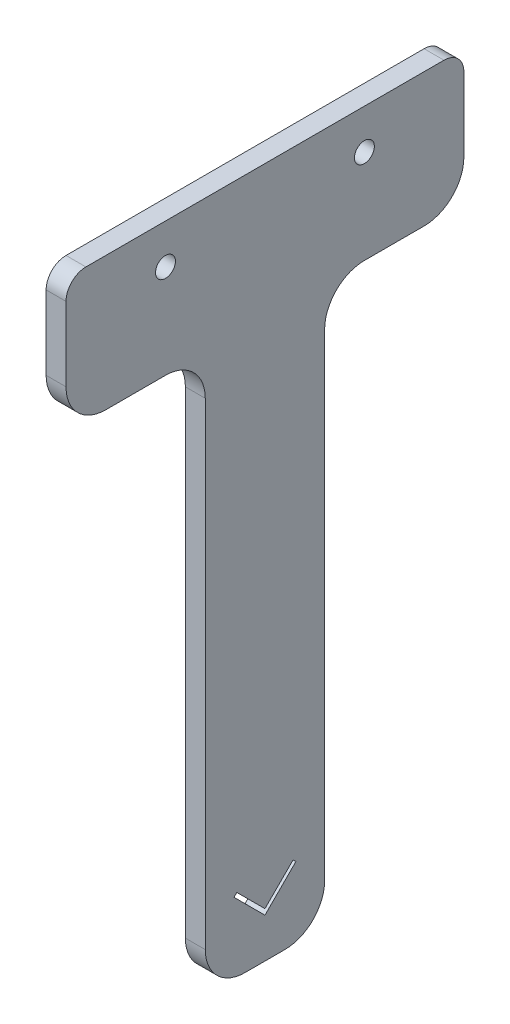
SolidWorks part; units mm, degrees
material "Balsa"
ref_plane "Front Plane" through (0, 0, 0) normal (0, 0, 1) x (1, 0, 0)
ref_plane "Top Plane" through (0, 0, 0) normal (0, 1, 0) x (1, 0, 0)
ref_plane "Right Plane" through (0, 0, 0) normal (1, 0, 0) x (0, 0, -1)
sketch "Sketch3" plane through (0, 0, 0) normal (1, 0, 0) x (0, 0, -1)
  line L1 (-57.15, -110.236) -> (57.15, -110.236)
  line L2 (-63.5, -103.886) -> (-63.5, 103.886)
  line L3 (-57.15, 110.236) -> (57.15, 110.236)
  line L4 (63.5, -103.886) -> (63.5, 103.886)
  line L5 (-63.5, -110.236) -> (63.5, 110.236) construction
  line L6 (-63.5, 110.236) -> (63.5, -110.236) construction
  line L11 (0, 0) -> (38.1, 84.836) construction
  line L12 (-38.1, 84.836) -> (0, 0) construction
  arc A0 (-57.15, -110.236) -> (-63.5, -103.886) centre (-57.15, -103.886) cw
  arc A1 (63.5, -103.886) -> (57.15, -110.236) centre (57.15, -103.886) cw
  arc A2 (63.5, 103.886) -> (57.15, 110.236) centre (57.15, 103.886) ccw
  arc A3 (-63.5, 103.886) -> (-57.15, 110.236) centre (-57.15, 103.886) cw
  point P0 (0, 0)
  point P6 (0, 0)
  point P26 (38.1, -67.564)
  dimension "D7" = 6.35
  dimension "D1" = 220.472
  dimension "D2" = 127
  dimension "D3" = 76.2
  dimension "D4" = 152.4
extrude "Boss-Extrude2" add sketch "Sketch3" along normal blind 6.35
sketch "Sketch4" plane through (6.35, 0, 0) normal (1, 0, 0) x (0, 0, -1)
  line L0 (-57.15, -110.236) -> (57.15, -110.236) construction
  line L5 (0, -95.7399) -> (-8.9803, -86.7597)
  line L6 (-8.9803, -86.7597) -> (-9.8783, -87.6577)
  line L8 (-9.8783, -87.6577) -> (0, -97.536)
  line L9 (0, -97.536) -> (9.8783, -87.6577)
  line L10 (9.8783, -87.6577) -> (8.9803, -86.7597)
  line L11 (8.9803, -86.7597) -> (0, -95.7399)
  line L12 (0, 55) -> (0, -55) construction
  dimension "D1" = 12.7
  dimension "D2" = 12.7
  dimension "D3" = 1.27
extrude "Cut-Extrude1" cut sketch "Sketch4" against normal up to next
sketch "Sketch5" plane through (6.35, 0, 0) normal (1, 0, 0) x (0, 0, -1)
  line L0 (-31.75, 97.536) -> (31.75, 97.536) construction
  line L1 (31.75, 97.536) -> (63.5, 97.536) construction
  line L2 (63.5, -103.886) -> (63.5, 103.886) construction
  line L3 (-31.75, 97.536) -> (-63.5, 97.536) construction
  line L4 (-63.5, 103.886) -> (-63.5, -103.886) construction
  line L5 (57.15, 110.236) -> (-57.15, 110.236) construction
  circle A0 centre (-31.75, 97.536) radius 3.175
  circle A1 centre (31.75, 97.536) radius 3.175
  dimension "D1" = 6.35
  dimension "D2" = 63.5
  dimension "D3" = 12.7
extrude "Cut-Extrude2" cut sketch "Sketch5" against normal through all both and the other way through all
sketch "Sketch6" plane through (6.35, 0, 0) normal (1, 0, 0) x (0, 0, -1)
  line L0 (-19.05, -97.536) -> (-19.05, 54.864)
  line L1 (19.05, -97.536) -> (19.05, 54.864)
  line L2 (0, 3.4925) -> (0, -3.4925) construction
  line L3 (-31.75, 67.564) -> (-50.8, 67.564)
  line L4 (-57.15, -110.236) -> (57.15, -110.236)
  line L5 (63.5, -103.886) -> (63.5, 103.886)
  line L6 (57.15, 110.236) -> (-57.15, 110.236)
  line L7 (-63.5, 103.886) -> (-63.5, -103.886)
  line L8 (-57.15, -110.236) -> (-19.05, -110.236)
  line L9 (63.5, -103.886) -> (63.5, 67.564)
  line L11 (-63.5, 67.564) -> (-63.5, -103.886)
  line L12 (31.75, 67.564) -> (50.8, 67.564)
  line L13 (19.05, -110.236) -> (57.15, -110.236)
  line L14 (-63.5, 80.264) -> (-63.5, 67.564)
  line L15 (63.5, 80.264) -> (63.5, 67.564)
  line L16 (6.35, -110.236) -> (19.05, -110.236)
  line L18 (-19.05, -110.236) -> (-6.35, -110.236)
  arc A0 (19.05, 54.864) -> (31.75, 67.564) centre (31.75, 54.864) cw
  arc A1 (-19.05, 54.864) -> (-31.75, 67.564) centre (-31.75, 54.864) ccw
  arc A2 (-63.5, 80.264) -> (-50.8, 67.564) centre (-50.8, 80.264) ccw
  arc A3 (63.5, 80.264) -> (50.8, 67.564) centre (50.8, 80.264) cw
  arc A4 (-63.5, -103.886) -> (-57.15, -110.236) centre (-57.15, -103.886) ccw
  arc A5 (57.15, -110.236) -> (63.5, -103.886) centre (57.15, -103.886) ccw
  arc A6 (63.5, 103.886) -> (57.15, 110.236) centre (57.15, 103.886) ccw
  arc A7 (-57.15, 110.236) -> (-63.5, 103.886) centre (-57.15, 103.886) ccw
  arc A8 (-63.5, -103.886) -> (-57.15, -110.236) centre (-57.15, -103.886) ccw
  arc A9 (57.15, -110.236) -> (63.5, -103.886) centre (57.15, -103.886) ccw
  arc A12 (6.35, -110.236) -> (19.05, -97.536) centre (6.35, -97.536) ccw
  arc A13 (-19.05, -97.536) -> (-6.35, -110.236) centre (-6.35, -97.536) ccw
  point P24 (-19.05, 67.564)
  dimension "D5" = 12.7
  dimension "D6" = 12.7
  dimension "D7" = 12.7
  dimension "D8" = 12.7
  dimension "D9" = 12.7
  dimension "D2" = 177.8
  dimension "D3" = 19.05
  dimension "D4" = 19.05
  dimension "D1" = 0
extrude "Cut-Extrude3" cut sketch "Sketch6" against normal through all
